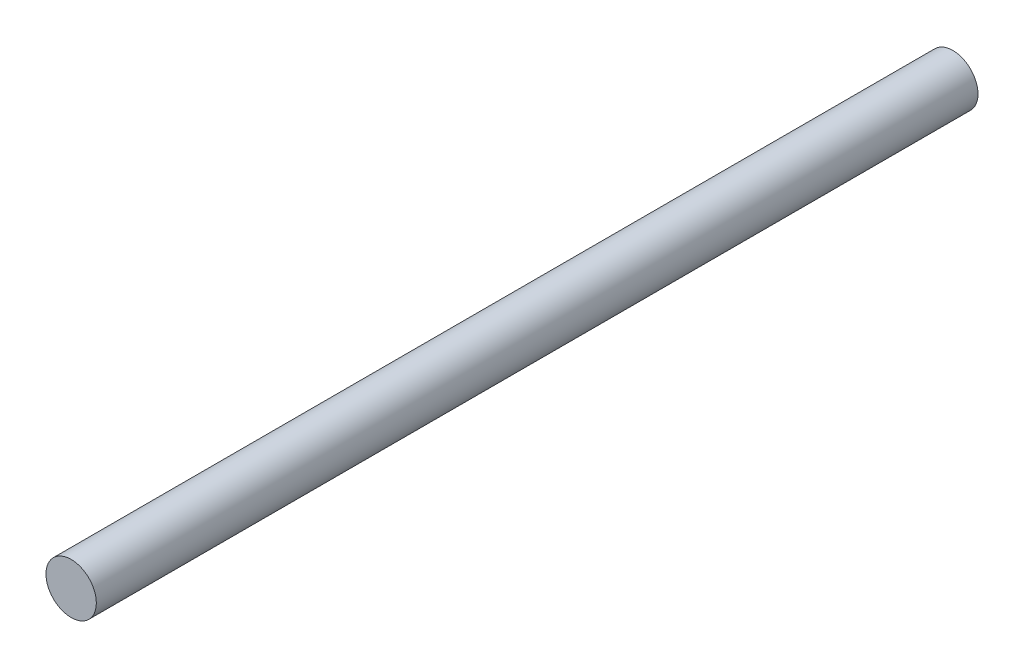
SolidWorks part; units mm, degrees
material "AISI 1020"
ref_plane "Plano frontal" through (0, 0, 0) normal (0, 0, 1) x (1, 0, 0)
ref_plane "Plano superior" through (0, 0, 0) normal (0, 1, 0) x (1, 0, 0)
ref_plane "Plano direito" through (0, 0, 0) normal (1, 0, 0) x (0, 0, -1)
sketch "Esboço1" plane through (0, 0, 0) normal (0, 0, 1) x (1, 0, 0)
  circle A0 centre (0, 0) radius 5
  dimension "D1" = 10
extrude "Ressalto-extrusão1" add sketch "Esboço1" along normal mid plane 175
